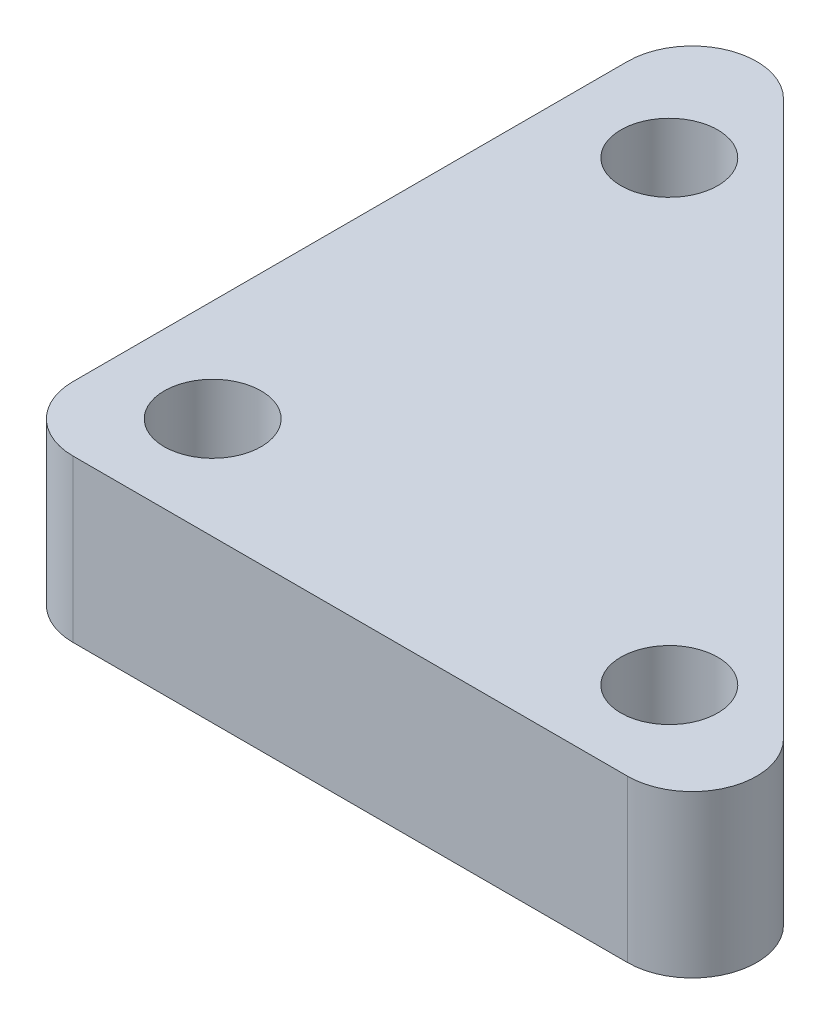
SolidWorks part; units mm, degrees
ref_plane "前视" through (0, 0, 0) normal (0, 0, 1) x (1, 0, 0)
ref_plane "上视" through (0, 0, 0) normal (0, 1, 0) x (1, 0, 0)
ref_plane "右视" through (0, 0, 0) normal (1, 0, 0) x (0, 0, -1)
sketch "Sketch1" plane through (0, 0, 0) normal (0, 1, 0) x (1, 0, 0)
  line L0 (-0.8134, -17.679) -> (23.1866, -17.679)
  line L1 (-0.8134, -17.679) -> (-0.8134, 6.321)
  line L2 (-0.8134, 6.321) -> (23.1866, -17.679)
  dimension "D1" = 24
  dimension "D2" = 24
  dimension "D3" = 33.9411
extrude "Boss-Extrude1" add sketch "Sketch1" along normal blind 5
fillet "Fillet1" radius 2 3 edges at (-0.8134, 2.5, 17.679) (-0.8134, 2.5, -6.321) (23.1866, 2.5, 17.679)
sketch "Sketch2" plane through (0, 5, 0) normal (0, 1, 0) x (1, 0, 0)
  line L2 (19.7724, -14.2648) -> (2.6008, 2.9067) construction
  circle A0 centre (2.3478, -14.5179) radius 1.5
  circle A1 centre (2.4182, -0.4462) radius 1.5
  circle A2 centre (16.5604, -14.5883) radius 1.5
  dimension "D1" = 12.5
  dimension "D3" = 2.5
  dimension "D4" = 2.5
  dimension "D5" = 20
extrude "Cut-Extrude1" cut sketch "Sketch2" against normal through all
